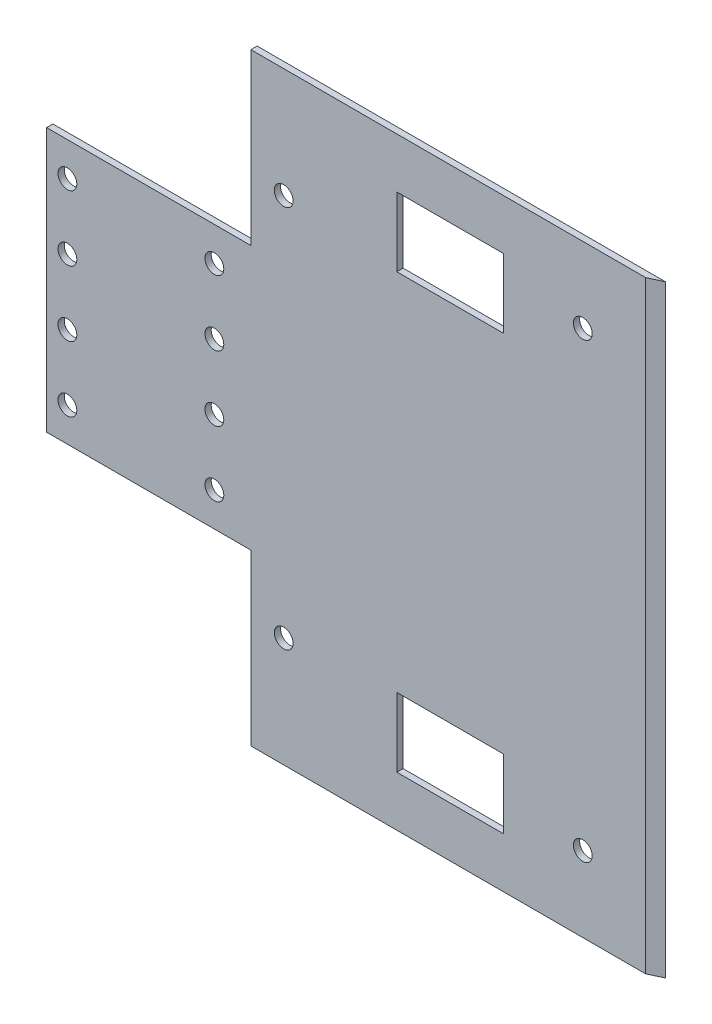
SolidWorks part; units mm, degrees
ref_plane "Спереди" through (0, 0, 0) normal (0, 0, 1) x (1, 0, 0)
ref_plane "Сверху" through (0, 0, 0) normal (0, 1, 0) x (1, 0, 0)
ref_plane "Справа" through (0, 0, 0) normal (1, 0, 0) x (0, 0, -1)
sketch "Эскиз1" plane through (0, 0, 0) normal (0, 0, 1) x (-1, 0, 0)
  line L1 (-25.2514, 40) -> (-8.2514, 40)
  line L2 (-25.2514, 40) -> (-25.2514, 29)
  line L3 (-25.2514, 29) -> (-8.2514, 29)
  line L4 (-8.2514, 40) -> (-8.2514, 29)
  line L5 (-25.2514, -29) -> (-8.2514, -29)
  line L6 (-25.2514, -29) -> (-25.2514, -40)
  line L7 (-25.2514, -40) -> (-8.2514, -40)
  line L8 (-8.2514, -29) -> (-8.2514, -40)
  line L16 (47.5, 21) -> (15, 21)
  line L17 (15, 21) -> (15, 48)
  line L18 (15, 48) -> (-50, 48)
  line L19 (-50, 48) -> (-50, -48)
  line L20 (-50, -48) -> (15, -48)
  line L21 (15, -48) -> (15, -21)
  line L22 (15, -21) -> (47.5, -21)
  line L23 (47.5, -21) -> (47.5, 21)
  circle A0 centre (20.8, -15.6) radius 1.5
  circle A1 centre (20.8, -5.2) radius 1.5
  circle A2 centre (20.8, 5.2) radius 1.5
  circle A3 centre (20.8, 15.6) radius 1.5
  circle A4 centre (44.2, -15.6) radius 1.5
  circle A5 centre (44.2, -5.2) radius 1.5
  circle A6 centre (44.2, 5.2) radius 1.5
  circle A7 centre (44.2, 15.6) radius 1.5
  circle A8 centre (9.7633, -30.5) radius 1.5
  circle A9 centre (9.7633, 30.5) radius 1.5
  circle A10 centre (-37.8555, -36) radius 1.5
  circle A11 centre (-37.8555, 36) radius 1.5
extrude "Бобышка-Вытянуть1" add sketch "Эскиз1" along normal blind 1 contours L21 L22 L23 L16 L17 L18 L19 L20
sketch "Эскиз2" plane through (0, 48, 0) normal (0, 1, 0) x (1, 0, 0)
  line L0 (47.8555, -1) -> (50, 0)
  line L2 (50, -1) -> (50, 0)
  line L4 (50, -1) -> (47.8555, -1)
extrude "Вырез-Вытянуть1" cut sketch "Эскиз2" against normal through all
